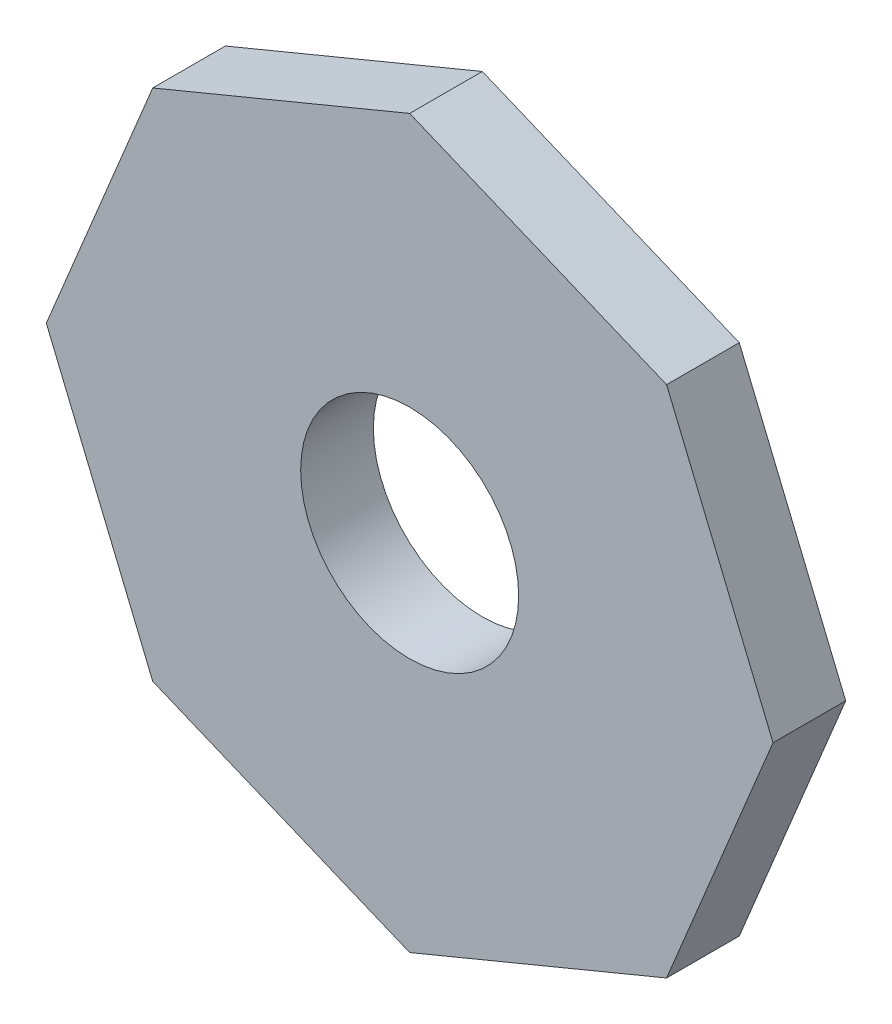
SolidWorks part; units mm, degrees
ref_plane "前视基准面" through (0, 0, 0) normal (0, 0, 1) x (1, 0, 0)
ref_plane "上视基准面" through (0, 0, 0) normal (0, 1, 0) x (1, 0, 0)
ref_plane "右视基准面" through (0, 0, 0) normal (1, 0, 0) x (0, 0, -1)
other "Configuration Table"
sketch "草图1" plane through (0, 0, 0) normal (0, 0, 1) x (1, 0, 0)
  line L1 (100, 0) -> (70.7107, 70.7107)
  line L2 (70.7107, 70.7107) -> (0, 100)
  line L3 (0, 100) -> (-70.7107, 70.7107)
  line L4 (-70.7107, 70.7107) -> (-100, 0)
  line L5 (-100, 0) -> (-70.7107, -70.7107)
  line L6 (-70.7107, -70.7107) -> (0, -100)
  line L7 (0, -100) -> (70.7107, -70.7107)
  line L8 (70.7107, -70.7107) -> (100, 0)
  circle A0 centre (0, 0) radius 92.388 construction
extrude "凸台-拉伸1" add sketch "草图1" along normal blind 20
sketch "草图2" plane through (0, 0, 0) normal (0, 0, 1) x (1, 0, 0)
  circle A0 centre (0, 0) radius 30
extrude "切除-拉伸2" cut sketch "草图2" along normal through all
